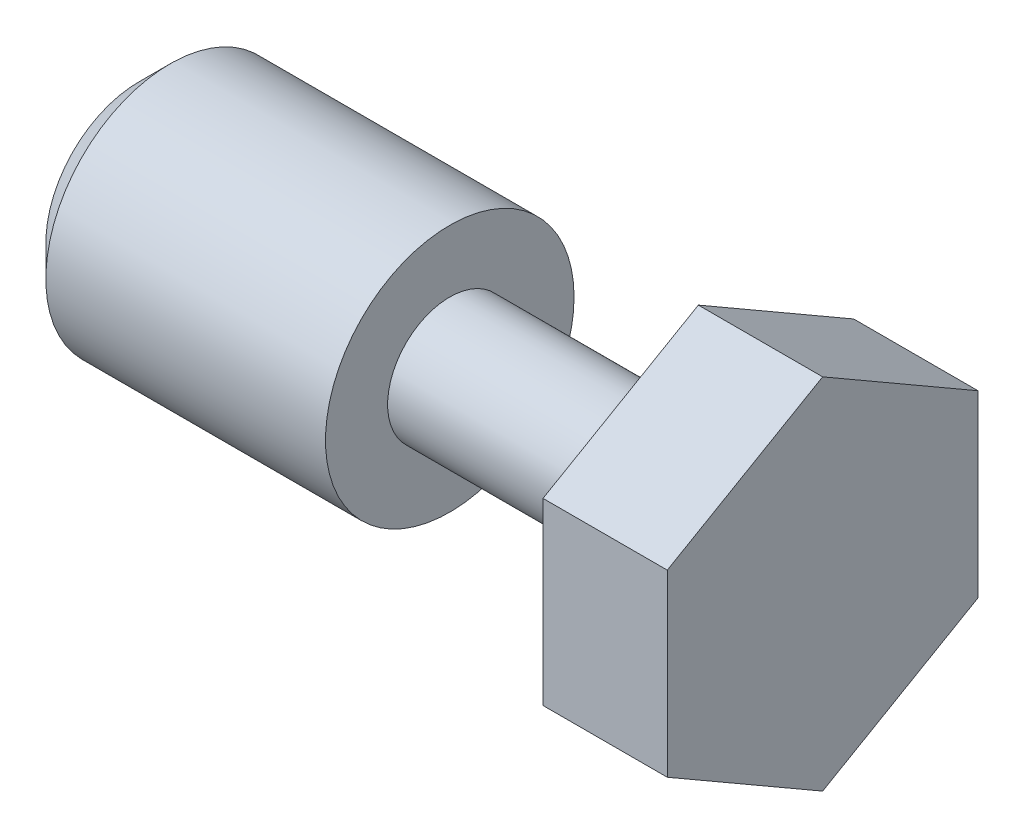
SolidWorks part; units mm, degrees
ref_plane "Front Plane" through (0, 0, 0) normal (0, 0, 1) x (1, 0, 0)
ref_plane "Top Plane" through (0, 0, 0) normal (0, 1, 0) x (1, 0, 0)
ref_plane "Right Plane" through (0, 0, 0) normal (1, 0, 0) x (0, 0, -1)
sketch "Sketch1" plane through (0, 0, 0) normal (1, 0, 0) x (0, 0, -1)
  circle A0 centre (0, 0) radius 2
  dimension "D1" = 4
extrude "Boss-Extrude1" add sketch "Sketch1" along normal blind 5
cosmetic thread "Cosmetic Thread4" parameters "D2"=3.242
sketch "Sketch3" plane through (5, 0, 0) normal (1, 0, 0) x (0, 0, -1)
  circle A0 centre (0, 0) radius 1
  dimension "2" = 2
extrude "Boss-Extrude2" add sketch "Sketch3" along normal blind 4
sketch "Sketch4" plane through (9, 0, 0) normal (1, 0, 0) x (0, 0, -1)
  line L1 (0, -2.8868) -> (2.5, -1.4434)
  line L2 (2.5, -1.4434) -> (2.5, 1.4434)
  line L3 (2.5, 1.4434) -> (0, 2.8868)
  line L4 (0, 2.8868) -> (-2.5, 1.4434)
  line L5 (-2.5, 1.4434) -> (-2.5, -1.4434)
  line L6 (-2.5, -1.4434) -> (0, -2.8868)
  circle A0 centre (0, 0) radius 2.5 construction
  dimension "D1" = 5
extrude "Boss-Extrude3" add sketch "Sketch4" along normal blind 2
chamfer "Chamfer1" distance 0.5 angle 45 1 edges at (0, 0, -2)
